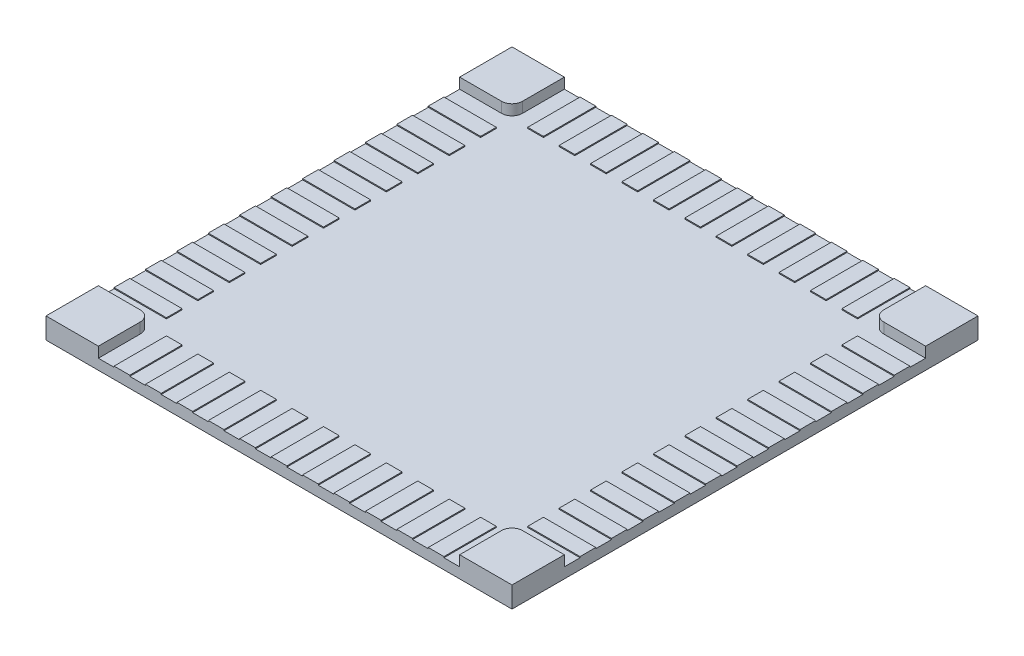
SolidWorks part; units mm, degrees
ref_plane "Front Plane" through (0, 0, 0) normal (0, 0, 1) x (1, 0, 0)
ref_plane "Top Plane" through (0, 0, 0) normal (0, 1, 0) x (1, 0, 0)
ref_plane "Right Plane" through (0, 0, 0) normal (1, 0, 0) x (0, 0, -1)
sketch "Sketch1" plane through (0, 0, 0) normal (0, 1, 0) x (1, 0, 0)
  line L0 (0, 141.0735) -> (0, -142.5743) construction
  line L1 (-171.6126, 0) -> (226.4698, 0) construction
  line L3 (-44.5, -44.5) -> (44.5, -44.5)
  line L4 (-44.5, -44.5) -> (-44.5, 44.5)
  line L5 (-44.5, 44.5) -> (44.5, 44.5)
  line L6 (44.5, -44.5) -> (44.5, 44.5)
  line L7 (-44.5, -44.5) -> (44.5, 44.5) construction
  line L8 (-44.5, 44.5) -> (44.5, -44.5) construction
  point P7 (0, 0)
  dimension "D1" = 89
extrude "Boss-Extrude1" add sketch "Sketch1" along normal blind 2
sketch "Sketch2" plane through (0, 2, 0) normal (0, 1, 0) x (1, 0, 0)
  line L0 (0, 49.3696) -> (0, -51.6137) construction
  line L1 (-55.4397, 0) -> (61.6302, 0) construction
  line L2 (44.5, 44.5) -> (-44.5, 44.5) construction
  line L3 (-44.5, 44.5) -> (-34.5, 44.5)
  line L4 (-44.5, 44.5) -> (-44.5, 34.5)
  line L5 (-44.5, 34.5) -> (-34.5, 34.5)
  line L6 (-34.5, 44.5) -> (-34.5, 34.5)
  line L7 (-44.5, 44.5) -> (-34.5, 34.5) construction
  line L8 (-44.5, 34.5) -> (-34.5, 44.5) construction
  line L9 (-44.5, 44.5) -> (-44.5, -44.5) construction
  line L10 (44.5, 34.5) -> (34.5, 44.5) construction
  line L11 (44.5, 44.5) -> (34.5, 34.5) construction
  line L12 (34.5, 44.5) -> (34.5, 34.5)
  line L13 (44.5, 34.5) -> (34.5, 34.5)
  line L14 (44.5, 44.5) -> (44.5, 34.5)
  line L15 (44.5, 44.5) -> (34.5, 44.5)
  line L16 (44.5, -44.5) -> (34.5, -34.5) construction
  line L17 (44.5, -34.5) -> (34.5, -44.5) construction
  line L18 (-44.5, -34.5) -> (-34.5, -44.5) construction
  line L19 (-44.5, -44.5) -> (-34.5, -34.5) construction
  line L20 (44.5, -44.5) -> (34.5, -44.5)
  line L21 (44.5, -44.5) -> (44.5, -34.5)
  line L22 (44.5, -34.5) -> (34.5, -34.5)
  line L23 (34.5, -44.5) -> (34.5, -34.5)
  line L24 (-34.5, -44.5) -> (-34.5, -34.5)
  line L25 (-44.5, -34.5) -> (-34.5, -34.5)
  line L26 (-44.5, -44.5) -> (-44.5, -34.5)
  line L27 (-44.5, -44.5) -> (-34.5, -44.5)
  point P5 (-39.5, 39.5)
  point P19 (39.5, 39.5)
  point P28 (39.5, -39.5)
  point P29 (-39.5, -39.5)
  dimension "D1" = 10
extrude "Boss-Extrude2" add sketch "Sketch2" along normal blind 2
sketch "Sketch3" plane through (0, 2, 0) normal (0, 1, 0) x (1, 0, 0)
  line L0 (0, 49.5736) -> (0, -53.4497) construction
  line L1 (-55.8978, 0) -> (52.2257, 0) construction
  line L2 (-34.5, 34.5) -> (-44.5, 34.5)
  line L3 (-44.5, 34.5) -> (-44.5, 31.5)
  line L4 (-44.5, 34.5) -> (-44.5, -34.5) construction
  line L5 (-44.5, 31.5) -> (-34.5, 31.5)
  line L6 (-34.5, 31.5) -> (-34.5, 34.5)
  line L7 (-34.5, 28.5) -> (-34.5, 31.5)
  line L8 (-44.5, 28.5) -> (-34.5, 28.5)
  line L9 (-44.5, 31.5) -> (-44.5, 28.5)
  line L10 (-34.5, 25.5) -> (-34.5, 28.5)
  line L11 (-44.5, 25.5) -> (-34.5, 25.5)
  line L12 (-44.5, 28.5) -> (-44.5, 25.5)
  line L13 (-34.5, 22.5) -> (-34.5, 25.5)
  line L14 (-44.5, 22.5) -> (-34.5, 22.5)
  line L15 (-44.5, 25.5) -> (-44.5, 22.5)
  line L16 (-34.5, 19.5) -> (-34.5, 22.5)
  line L17 (-44.5, 19.5) -> (-34.5, 19.5)
  line L18 (-44.5, 22.5) -> (-44.5, 19.5)
  line L19 (-34.5, 16.5) -> (-34.5, 19.5)
  line L20 (-44.5, 16.5) -> (-34.5, 16.5)
  line L21 (-44.5, 19.5) -> (-44.5, 16.5)
  line L22 (-34.5, 13.5) -> (-34.5, 16.5)
  line L23 (-44.5, 13.5) -> (-34.5, 13.5)
  line L24 (-44.5, 16.5) -> (-44.5, 13.5)
  line L25 (-34.5, 10.5) -> (-34.5, 13.5)
  line L26 (-44.5, 10.5) -> (-34.5, 10.5)
  line L27 (-44.5, 13.5) -> (-44.5, 10.5)
  line L28 (-34.5, 7.5) -> (-34.5, 10.5)
  line L29 (-44.5, 7.5) -> (-34.5, 7.5)
  line L30 (-44.5, 10.5) -> (-44.5, 7.5)
  line L31 (-34.5, 4.5) -> (-34.5, 7.5)
  line L32 (-44.5, 4.5) -> (-34.5, 4.5)
  line L33 (-44.5, 7.5) -> (-44.5, 4.5)
  line L34 (-34.5, 1.5) -> (-34.5, 4.5)
  line L35 (-44.5, 1.5) -> (-34.5, 1.5)
  line L36 (-44.5, 4.5) -> (-44.5, 1.5)
  line L37 (-34.5, -1.5) -> (-34.5, 1.5)
  line L38 (-44.5, -1.5) -> (-34.5, -1.5)
  line L39 (-44.5, 1.5) -> (-44.5, -1.5)
  line L40 (-34.5, -4.5) -> (-34.5, -1.5)
  line L41 (-44.5, -4.5) -> (-34.5, -4.5)
  line L42 (-44.5, -1.5) -> (-44.5, -4.5)
  line L43 (-34.5, -7.5) -> (-34.5, -4.5)
  line L44 (-44.5, -7.5) -> (-34.5, -7.5)
  line L45 (-44.5, -4.5) -> (-44.5, -7.5)
  line L46 (-34.5, -10.5) -> (-34.5, -7.5)
  line L47 (-44.5, -10.5) -> (-34.5, -10.5)
  line L48 (-44.5, -7.5) -> (-44.5, -10.5)
  line L49 (-34.5, -13.5) -> (-34.5, -10.5)
  line L50 (-44.5, -13.5) -> (-34.5, -13.5)
  line L51 (-44.5, -10.5) -> (-44.5, -13.5)
  line L52 (-34.5, -16.5) -> (-34.5, -13.5)
  line L53 (-44.5, -16.5) -> (-34.5, -16.5)
  line L54 (-44.5, -13.5) -> (-44.5, -16.5)
  line L55 (-34.5, -19.5) -> (-34.5, -16.5)
  line L56 (-44.5, -19.5) -> (-34.5, -19.5)
  line L57 (-44.5, -16.5) -> (-44.5, -19.5)
  line L58 (-34.5, -22.5) -> (-34.5, -19.5)
  line L59 (-44.5, -22.5) -> (-34.5, -22.5)
  line L60 (-44.5, -19.5) -> (-44.5, -22.5)
  line L61 (-34.5, -25.5) -> (-34.5, -22.5)
  line L62 (-44.5, -25.5) -> (-34.5, -25.5)
  line L63 (-44.5, -22.5) -> (-44.5, -25.5)
  line L64 (-34.5, -28.5) -> (-34.5, -25.5)
  line L65 (-44.5, -28.5) -> (-34.5, -28.5)
  line L66 (-44.5, -25.5) -> (-44.5, -28.5)
  line L67 (-34.5, -31.5) -> (-34.5, -28.5)
  line L68 (-44.5, -31.5) -> (-34.5, -31.5)
  line L69 (-44.5, -28.5) -> (-44.5, -31.5)
  line L70 (-34.5, -34.5) -> (-34.5, -31.5)
  line L71 (-44.5, -34.5) -> (-34.5, -34.5)
  line L72 (-44.5, -31.5) -> (-44.5, -34.5)
  line L73 (-34.5, -34.5) -> (-44.5, -34.5) construction
  line L74 (34.5, 34.5) -> (34.5, 44.5)
  line L75 (34.5, 44.5) -> (31.5, 44.5)
  line L76 (31.5, 44.5) -> (31.5, 34.5)
  line L77 (31.5, 34.5) -> (34.5, 34.5)
  line L78 (28.5, 34.5) -> (31.5, 34.5)
  line L79 (28.5, 44.5) -> (28.5, 34.5)
  line L80 (31.5, 44.5) -> (28.5, 44.5)
  line L81 (25.5, 34.5) -> (28.5, 34.5)
  line L82 (25.5, 44.5) -> (25.5, 34.5)
  line L83 (28.5, 44.5) -> (25.5, 44.5)
  line L84 (22.5, 34.5) -> (25.5, 34.5)
  line L85 (22.5, 44.5) -> (22.5, 34.5)
  line L86 (25.5, 44.5) -> (22.5, 44.5)
  line L87 (19.5, 34.5) -> (22.5, 34.5)
  line L88 (19.5, 44.5) -> (19.5, 34.5)
  line L89 (22.5, 44.5) -> (19.5, 44.5)
  line L90 (16.5, 34.5) -> (19.5, 34.5)
  line L91 (16.5, 44.5) -> (16.5, 34.5)
  line L92 (19.5, 44.5) -> (16.5, 44.5)
  line L93 (13.5, 34.5) -> (16.5, 34.5)
  line L94 (13.5, 44.5) -> (13.5, 34.5)
  line L95 (16.5, 44.5) -> (13.5, 44.5)
  line L96 (10.5, 34.5) -> (13.5, 34.5)
  line L97 (10.5, 44.5) -> (10.5, 34.5)
  line L98 (13.5, 44.5) -> (10.5, 44.5)
  line L99 (7.5, 34.5) -> (10.5, 34.5)
  line L100 (7.5, 44.5) -> (7.5, 34.5)
  line L101 (10.5, 44.5) -> (7.5, 44.5)
  line L102 (4.5, 34.5) -> (7.5, 34.5)
  line L103 (4.5, 44.5) -> (4.5, 34.5)
  line L104 (7.5, 44.5) -> (4.5, 44.5)
  line L105 (1.5, 34.5) -> (4.5, 34.5)
  line L106 (1.5, 44.5) -> (1.5, 34.5)
  line L107 (4.5, 44.5) -> (1.5, 44.5)
  line L108 (-1.5, 34.5) -> (1.5, 34.5)
  line L109 (-1.5, 44.5) -> (-1.5, 34.5)
  line L110 (1.5, 44.5) -> (-1.5, 44.5)
  line L111 (-4.5, 34.5) -> (-1.5, 34.5)
  line L112 (-4.5, 44.5) -> (-4.5, 34.5)
  line L113 (-1.5, 44.5) -> (-4.5, 44.5)
  line L114 (-7.5, 34.5) -> (-4.5, 34.5)
  line L115 (-7.5, 44.5) -> (-7.5, 34.5)
  line L116 (-4.5, 44.5) -> (-7.5, 44.5)
  line L117 (-10.5, 34.5) -> (-7.5, 34.5)
  line L118 (-10.5, 44.5) -> (-10.5, 34.5)
  line L119 (-7.5, 44.5) -> (-10.5, 44.5)
  line L120 (-13.5, 34.5) -> (-10.5, 34.5)
  line L121 (-13.5, 44.5) -> (-13.5, 34.5)
  line L122 (-10.5, 44.5) -> (-13.5, 44.5)
  line L123 (-16.5, 34.5) -> (-13.5, 34.5)
  line L124 (-16.5, 44.5) -> (-16.5, 34.5)
  line L125 (-13.5, 44.5) -> (-16.5, 44.5)
  line L126 (-19.5, 34.5) -> (-16.5, 34.5)
  line L127 (-19.5, 44.5) -> (-19.5, 34.5)
  line L128 (-16.5, 44.5) -> (-19.5, 44.5)
  line L129 (-22.5, 34.5) -> (-19.5, 34.5)
  line L130 (-22.5, 44.5) -> (-22.5, 34.5)
  line L131 (-19.5, 44.5) -> (-22.5, 44.5)
  line L132 (-25.5, 34.5) -> (-22.5, 34.5)
  line L133 (-25.5, 44.5) -> (-25.5, 34.5)
  line L134 (-22.5, 44.5) -> (-25.5, 44.5)
  line L135 (-28.5, 34.5) -> (-25.5, 34.5)
  line L136 (-28.5, 44.5) -> (-28.5, 34.5)
  line L137 (-25.5, 44.5) -> (-28.5, 44.5)
  line L138 (-31.5, 34.5) -> (-28.5, 34.5)
  line L139 (-31.5, 44.5) -> (-31.5, 34.5)
  line L140 (-28.5, 44.5) -> (-31.5, 44.5)
  line L141 (-34.5, 34.5) -> (-31.5, 34.5)
  line L142 (-34.5, 44.5) -> (-34.5, 34.5)
  line L143 (-31.5, 44.5) -> (-34.5, 44.5)
  line L144 (34.5, -34.5) -> (44.5, -34.5)
  line L145 (44.5, -34.5) -> (44.5, -31.5)
  line L146 (44.5, -31.5) -> (34.5, -31.5)
  line L147 (34.5, -31.5) -> (34.5, -34.5)
  line L148 (34.5, -28.5) -> (34.5, -31.5)
  line L149 (44.5, -28.5) -> (34.5, -28.5)
  line L150 (44.5, -31.5) -> (44.5, -28.5)
  line L151 (34.5, -25.5) -> (34.5, -28.5)
  line L152 (44.5, -25.5) -> (34.5, -25.5)
  line L153 (44.5, -28.5) -> (44.5, -25.5)
  line L154 (34.5, -22.5) -> (34.5, -25.5)
  line L155 (44.5, -22.5) -> (34.5, -22.5)
  line L156 (44.5, -25.5) -> (44.5, -22.5)
  line L157 (34.5, -19.5) -> (34.5, -22.5)
  line L158 (44.5, -19.5) -> (34.5, -19.5)
  line L159 (44.5, -22.5) -> (44.5, -19.5)
  line L160 (34.5, -16.5) -> (34.5, -19.5)
  line L161 (44.5, -16.5) -> (34.5, -16.5)
  line L162 (44.5, -19.5) -> (44.5, -16.5)
  line L163 (34.5, -13.5) -> (34.5, -16.5)
  line L164 (44.5, -13.5) -> (34.5, -13.5)
  line L165 (44.5, -16.5) -> (44.5, -13.5)
  line L166 (34.5, -10.5) -> (34.5, -13.5)
  line L167 (44.5, -10.5) -> (34.5, -10.5)
  line L168 (44.5, -13.5) -> (44.5, -10.5)
  line L169 (34.5, -7.5) -> (34.5, -10.5)
  line L170 (44.5, -7.5) -> (34.5, -7.5)
  line L171 (44.5, -10.5) -> (44.5, -7.5)
  line L172 (34.5, -4.5) -> (34.5, -7.5)
  line L173 (44.5, -4.5) -> (34.5, -4.5)
  line L174 (44.5, -7.5) -> (44.5, -4.5)
  line L175 (34.5, -1.5) -> (34.5, -4.5)
  line L176 (44.5, -1.5) -> (34.5, -1.5)
  line L177 (44.5, -4.5) -> (44.5, -1.5)
  line L178 (34.5, 1.5) -> (34.5, -1.5)
  line L179 (44.5, 1.5) -> (34.5, 1.5)
  line L180 (44.5, -1.5) -> (44.5, 1.5)
  line L181 (34.5, 4.5) -> (34.5, 1.5)
  line L182 (44.5, 4.5) -> (34.5, 4.5)
  line L183 (44.5, 1.5) -> (44.5, 4.5)
  line L184 (34.5, 7.5) -> (34.5, 4.5)
  line L185 (44.5, 7.5) -> (34.5, 7.5)
  line L186 (44.5, 4.5) -> (44.5, 7.5)
  line L187 (34.5, 10.5) -> (34.5, 7.5)
  line L188 (44.5, 10.5) -> (34.5, 10.5)
  line L189 (44.5, 7.5) -> (44.5, 10.5)
  line L190 (34.5, 13.5) -> (34.5, 10.5)
  line L191 (44.5, 13.5) -> (34.5, 13.5)
  line L192 (44.5, 10.5) -> (44.5, 13.5)
  line L193 (34.5, 16.5) -> (34.5, 13.5)
  line L194 (44.5, 16.5) -> (34.5, 16.5)
  line L195 (44.5, 13.5) -> (44.5, 16.5)
  line L196 (34.5, 19.5) -> (34.5, 16.5)
  line L197 (44.5, 19.5) -> (34.5, 19.5)
  line L198 (44.5, 16.5) -> (44.5, 19.5)
  line L199 (34.5, 22.5) -> (34.5, 19.5)
  line L200 (44.5, 22.5) -> (34.5, 22.5)
  line L201 (44.5, 19.5) -> (44.5, 22.5)
  line L202 (34.5, 25.5) -> (34.5, 22.5)
  line L203 (44.5, 25.5) -> (34.5, 25.5)
  line L204 (44.5, 22.5) -> (44.5, 25.5)
  line L205 (34.5, 28.5) -> (34.5, 25.5)
  line L206 (44.5, 28.5) -> (34.5, 28.5)
  line L207 (44.5, 25.5) -> (44.5, 28.5)
  line L208 (34.5, 31.5) -> (34.5, 28.5)
  line L209 (44.5, 31.5) -> (34.5, 31.5)
  line L210 (44.5, 28.5) -> (44.5, 31.5)
  line L211 (34.5, 34.5) -> (34.5, 31.5)
  line L212 (44.5, 34.5) -> (34.5, 34.5)
  line L213 (44.5, 31.5) -> (44.5, 34.5)
  line L214 (-34.5, -34.5) -> (-34.5, -44.5)
  line L215 (-34.5, -44.5) -> (-31.5, -44.5)
  line L216 (-31.5, -44.5) -> (-31.5, -34.5)
  line L217 (-31.5, -34.5) -> (-34.5, -34.5)
  line L218 (-28.5, -34.5) -> (-31.5, -34.5)
  line L219 (-28.5, -44.5) -> (-28.5, -34.5)
  line L220 (-31.5, -44.5) -> (-28.5, -44.5)
  line L221 (-25.5, -34.5) -> (-28.5, -34.5)
  line L222 (-25.5, -44.5) -> (-25.5, -34.5)
  line L223 (-28.5, -44.5) -> (-25.5, -44.5)
  line L224 (-22.5, -34.5) -> (-25.5, -34.5)
  line L225 (-22.5, -44.5) -> (-22.5, -34.5)
  line L226 (-25.5, -44.5) -> (-22.5, -44.5)
  line L227 (-19.5, -34.5) -> (-22.5, -34.5)
  line L228 (-19.5, -44.5) -> (-19.5, -34.5)
  line L229 (-22.5, -44.5) -> (-19.5, -44.5)
  line L230 (-16.5, -34.5) -> (-19.5, -34.5)
  line L231 (-16.5, -44.5) -> (-16.5, -34.5)
  line L232 (-19.5, -44.5) -> (-16.5, -44.5)
  line L233 (-13.5, -34.5) -> (-16.5, -34.5)
  line L234 (-13.5, -44.5) -> (-13.5, -34.5)
  line L235 (-16.5, -44.5) -> (-13.5, -44.5)
  line L236 (-10.5, -34.5) -> (-13.5, -34.5)
  line L237 (-10.5, -44.5) -> (-10.5, -34.5)
  line L238 (-13.5, -44.5) -> (-10.5, -44.5)
  line L239 (-7.5, -34.5) -> (-10.5, -34.5)
  line L240 (-7.5, -44.5) -> (-7.5, -34.5)
  line L241 (-10.5, -44.5) -> (-7.5, -44.5)
  line L242 (-4.5, -34.5) -> (-7.5, -34.5)
  line L243 (-4.5, -44.5) -> (-4.5, -34.5)
  line L244 (-7.5, -44.5) -> (-4.5, -44.5)
  line L245 (-1.5, -34.5) -> (-4.5, -34.5)
  line L246 (-1.5, -44.5) -> (-1.5, -34.5)
  line L247 (-4.5, -44.5) -> (-1.5, -44.5)
  line L248 (1.5, -34.5) -> (-1.5, -34.5)
  line L249 (1.5, -44.5) -> (1.5, -34.5)
  line L250 (-1.5, -44.5) -> (1.5, -44.5)
  line L251 (4.5, -34.5) -> (1.5, -34.5)
  line L252 (4.5, -44.5) -> (4.5, -34.5)
  line L253 (1.5, -44.5) -> (4.5, -44.5)
  line L254 (7.5, -34.5) -> (4.5, -34.5)
  line L255 (7.5, -44.5) -> (7.5, -34.5)
  line L256 (4.5, -44.5) -> (7.5, -44.5)
  line L257 (10.5, -34.5) -> (7.5, -34.5)
  line L258 (10.5, -44.5) -> (10.5, -34.5)
  line L259 (7.5, -44.5) -> (10.5, -44.5)
  line L260 (13.5, -34.5) -> (10.5, -34.5)
  line L261 (13.5, -44.5) -> (13.5, -34.5)
  line L262 (10.5, -44.5) -> (13.5, -44.5)
  line L263 (16.5, -34.5) -> (13.5, -34.5)
  line L264 (16.5, -44.5) -> (16.5, -34.5)
  line L265 (13.5, -44.5) -> (16.5, -44.5)
  line L266 (19.5, -34.5) -> (16.5, -34.5)
  line L267 (19.5, -44.5) -> (19.5, -34.5)
  line L268 (16.5, -44.5) -> (19.5, -44.5)
  line L269 (22.5, -34.5) -> (19.5, -34.5)
  line L270 (22.5, -44.5) -> (22.5, -34.5)
  line L271 (19.5, -44.5) -> (22.5, -44.5)
  line L272 (25.5, -34.5) -> (22.5, -34.5)
  line L273 (25.5, -44.5) -> (25.5, -34.5)
  line L274 (22.5, -44.5) -> (25.5, -44.5)
  line L275 (28.5, -34.5) -> (25.5, -34.5)
  line L276 (28.5, -44.5) -> (28.5, -34.5)
  line L277 (25.5, -44.5) -> (28.5, -44.5)
  line L278 (31.5, -34.5) -> (28.5, -34.5)
  line L279 (31.5, -44.5) -> (31.5, -34.5)
  line L280 (28.5, -44.5) -> (31.5, -44.5)
  line L281 (34.5, -34.5) -> (31.5, -34.5)
  line L282 (34.5, -44.5) -> (34.5, -34.5)
  line L283 (31.5, -44.5) -> (34.5, -44.5)
  line L284 (44.5, -34.5) -> (34.5, -34.5) construction
  line L285 (44.5, -44.5) -> (44.5, 44.5) construction
  point P382 (0, 0)
  line M10 (-34.5, -44.5) -> (34.5, -44.5)
  line M13 (44.5, -34.5) -> (44.5, 34.5)
  line M16 (34.5, 44.5) -> (-34.5, 44.5)
  line M19 (-44.5, 34.5) -> (-44.5, -34.5)
  dimension "D1" = 3
  dimension "D2" = 23
  dimension "D3" = 4
extrude "Boss-Extrude3" add sketch "Sketch3" along normal blind 0.2 contours L8 L7 L5 M19 | L14 L13 L11 M19 | L20 L19 L17 M19 | L26 L25 L23 M19 | L32 L31 L29 M19 | L38 L37 L35 M19 | L44 L43 L41 M19 | L50 L49 L47 M19 | L56 L55 L53 M19 | L62 L61 L59 M19 | L68 L67 L65 M19 | L219 L218 L216 M10 | L225 L224 L222 M10 | L231 L230 L228 M10 | L237 L236 L234 M10 | L243 L242 L240 M10 | L249 L248 L246 M10 | L255 L254 L252 M10 | L261 L260 L258 M10 | L267 L266 L264 M10 | L273 L272 L270 M10 | L279 L278 L276 M10 | L149 L148 L146 M13 | L155 L154 L152 M13 | L161 L160 L158 M13 | L167 L166 L164 M13 | L173 L172 L170 M13 | L179 L178 L176 M13 | L185 L184 L182 M13 | L191 L190 L188 M13 | L197 L196 L194 M13 | L203 L202 L200 M13 | L209 L208 L206 M13 | L79 L78 L76 M16 | L85 L84 L82 M16 | L91 L90 L88 M16 | L97 L96 L94 M16 | L103 L102 L100 M16 | L109 L108 L106 M16 | L115 L114 L112 M16 | L121 L120 L118 M16 | L127 L126 L124 M16 | L133 L132 L130 M16 | L139 L138 L136 M16
fillet "Fillet1" radius 2 4 edges at (-34.5, 3, 34.5) (34.5, 3, 34.5) (34.5, 3, -34.5) (-34.5, 3, -34.5)
